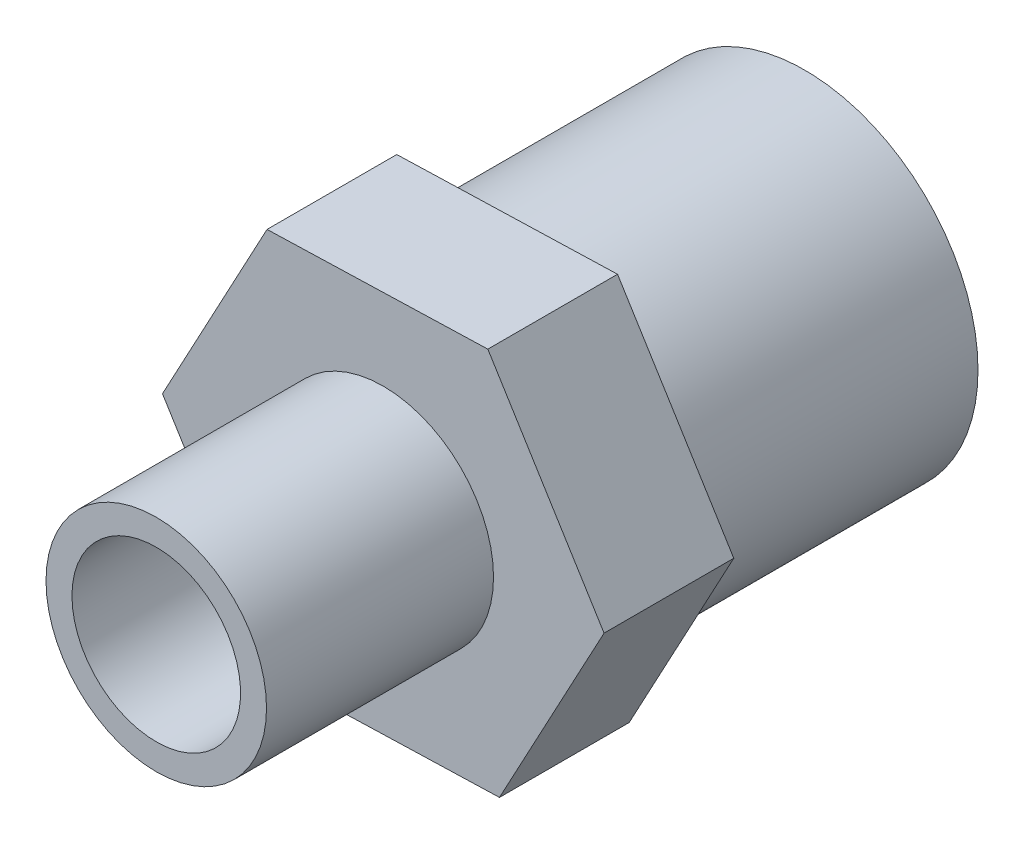
SolidWorks part; units mm, degrees
ref_plane "Front Plane" through (0, 0, 0) normal (0, 0, 1) x (1, 0, 0)
ref_plane "Top Plane" through (0, 0, 0) normal (0, 1, 0) x (1, 0, 0)
ref_plane "Right Plane" through (0, 0, 0) normal (1, 0, 0) x (0, 0, -1)
sketch "Sketch1" plane through (0, 0, 0) normal (0, 0, 1) x (1, 0, 0)
  circle A0 centre (0, 0) radius 8.5
  dimension "D1" = 17
extrude "Extrude-Thin1" add sketch "Sketch1" along normal blind 22.5 thin thin type one direction reverse wall 2
sketch "Sketch2" plane through (0, 0, 0) normal (0, 0, 1) x (1, 0, 0)
  line L1 (17.0215, 0.5179) -> (8.0622, 15)
  line L2 (8.0622, 15) -> (-8.9593, 14.4821)
  line L3 (-8.9593, 14.4821) -> (-17.0215, -0.5179)
  line L4 (-17.0215, -0.5179) -> (-8.0622, -15)
  line L5 (-8.0622, -15) -> (8.9593, -14.4821)
  line L6 (8.9593, -14.4821) -> (17.0215, 0.5179)
  circle A0 centre (0, 0) radius 14.7479 construction
  dimension "D1" = 15
extrude "Boss-Extrude1" add sketch "Sketch2" along normal mid plane 10
sketch "Sketch3" plane through (0, 0, -5) normal (0, 0, -1) x (-1, 0, 0)
  circle A0 centre (0, 0) radius 13.35
  dimension "D1" = 26.7
extrude "Extrude-Thin2" add sketch "Sketch3" along normal blind 22.5 thin thin type one direction reverse wall 2.7
